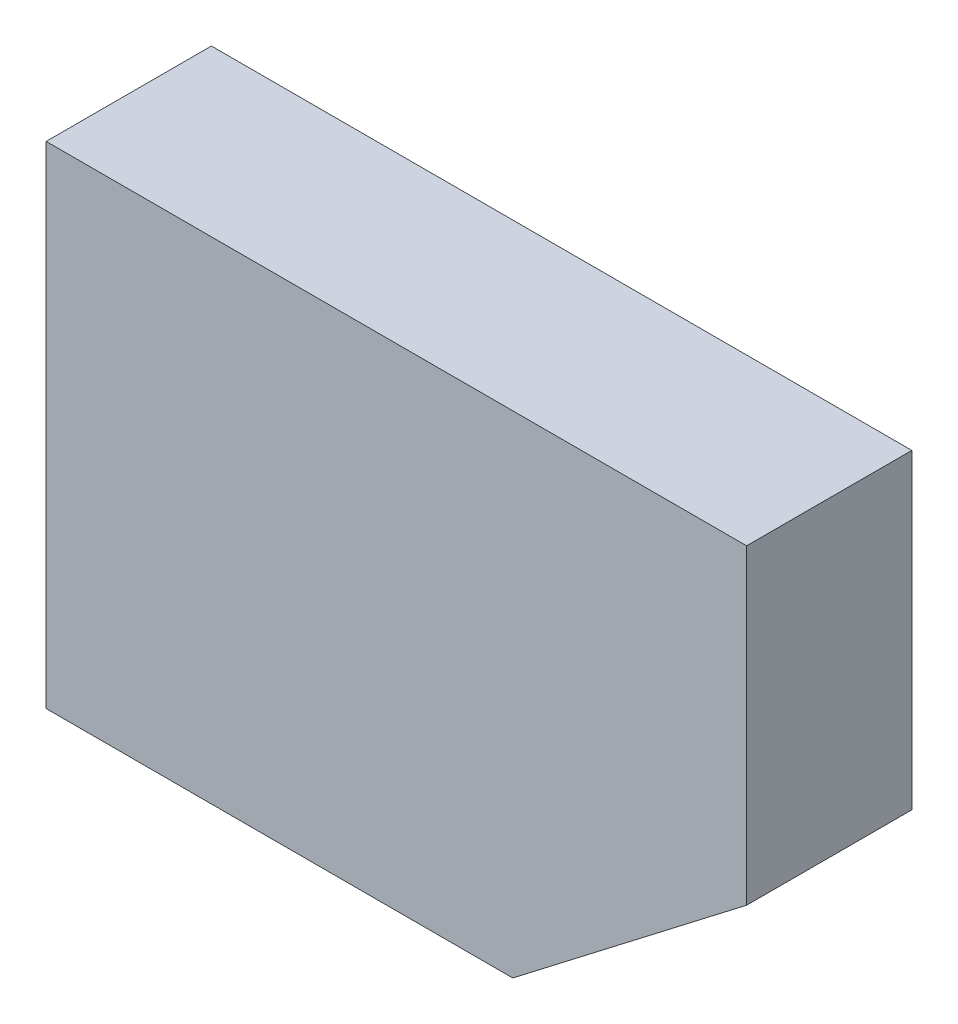
SolidWorks part; units mm, degrees
ref_plane "Спереди" through (0, 0, 0) normal (0, 0, 1) x (1, 0, 0)
ref_plane "Сверху" through (0, 0, 0) normal (0, 1, 0) x (1, 0, 0)
ref_plane "Справа" through (0, 0, 0) normal (1, 0, 0) x (0, 0, -1)
sketch "Эскиз1" plane through (0, 0, 0) normal (0, 0, 1) x (1, 0, 0)
  line L0 (-210, 0) -> (-210, -41.1667)
  line L1 (-210, 0) -> (-156.5, 0)
  line L2 (-156.5, 0) -> (-210, -41.1667)
  line L3 (-210, 10.6163) -> (-210, -27.7837) construction
  line L4 (-189, 0) -> (-124, 0) construction
extrude "Вытянуть1" add sketch "Эскиз1" along normal blind 8
sketch "Эскиз2" plane through (0, 0, 8) normal (0, 0, 1) x (1, 0, 0)
  line L0 (-210, -23.7828) -> (-184.7031, -23.7828)
  line L1 (-184.7031, -23.7828) -> (-184.7031, -45.7682)
  line L2 (-184.7031, -45.7682) -> (-210, -45.7682)
  line L3 (-210, -45.7682) -> (-210, -23.7828)
  line L8 (-210, 0) -> (-210, -41.1667) construction
  line L12 (-156.5, 4.6016) -> (-156.5, -16.8553)
  line L13 (-156.5, -16.8553) -> (-176.0857, -16.8553)
  line L14 (-176.0857, -16.8553) -> (-176.0857, 4.6016)
  line L15 (-176.0857, 4.6016) -> (-156.5, 4.6016)
extrude "Вырез-Вытянуть1" cut sketch "Эскиз2" against normal through all
